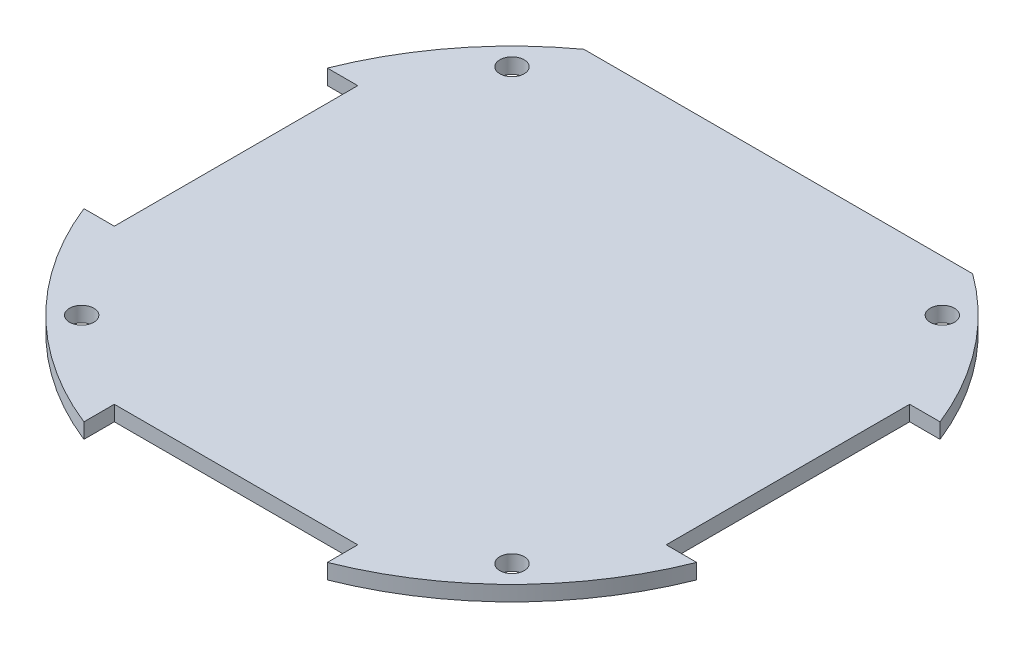
SolidWorks part; units mm, degrees
ref_plane "前视基准面" through (0, 0, 0) normal (0, 0, 1) x (1, 0, 0)
ref_plane "上视基准面" through (0, 0, 0) normal (0, 1, 0) x (1, 0, 0)
ref_plane "右视基准面" through (0, 0, 0) normal (1, 0, 0) x (0, 0, -1)
other "Configuration Table"
sketch "草图1" plane through (0, 0, 0) normal (0, 1, 0) x (1, 0, 0)
  circle A0 centre (0, 0) radius 32.5
  circle A1 centre (0, 0) radius 30 construction
  circle A3 centre (21.2132, 21.2132) radius 1.2
  circle A5 centre (21.2132, -21.2132) radius 1.2
  circle A7 centre (-21.2132, -21.2132) radius 1.2
  circle A9 centre (-21.2132, 21.2132) radius 1.2
  point P15 (0, 0)
  dimension "D1" = 65
  dimension "D2" = 60
extrude "凸台-拉伸1" add sketch "草图1" along normal blind 1.5
sketch "草图2" plane through (0, 1.5, 0) normal (0, 1, 0) x (1, 0, 0)
  line L0 (34.4418, 0) -> (-43.9173, 0) construction
  line L1 (30.2035, 12) -> (27.2035, 12)
  line L2 (27.2035, 12) -> (27.2035, -12)
  line L3 (30.2035, -12) -> (27.2035, -12)
  line L4 (0, 22.8929) -> (0, -32.5) construction
  line L8 (12, -27.2035) -> (-12, -27.2035)
  line L9 (-12, -30.2035) -> (-12, -27.2035)
  line L10 (12, -30.2035) -> (12, -27.2035)
  line L11 (-27.2035, -12) -> (-27.2035, 12)
  line L12 (-30.2035, 12) -> (-27.2035, 12)
  line L13 (-30.2035, -12) -> (-27.2035, -12)
  line L14 (-12, 27.2035) -> (12, 27.2035)
  line L15 (12, 30.2035) -> (12, 27.2035)
  line L16 (-12, 30.2035) -> (-12, 27.2035)
  circle A0 centre (0, 0) radius 32.5 construction
  arc A1 (30.2035, -12) -> (30.2035, 12) centre (0, 0) ccw
  arc A3 (-12, -30.2035) -> (12, -30.2035) centre (0, 0) ccw
  arc A4 (-30.2035, 12) -> (-30.2035, -12) centre (0, 0) ccw
  arc A5 (12, 30.2035) -> (-12, 30.2035) centre (0, 0) ccw
  point P9 (27.2035, 0)
  point P27 (0, 0)
  dimension "D1" = 12
  dimension "D2" = 3
  dimension "D3" = 4
extrude "切除-拉伸1" cut sketch "草图2" against normal through all
sketch "草图3" plane through (0, 1.5, 0) normal (0, 1, 0) x (1, 0, 0)
  line L1 (17, 26.25) -> (-17, 26.25)
  line L2 (17, 26.25) -> (28.1494, 26.25)
  line L3 (28.1494, 26.25) -> (-14.2404, 46.7454)
  line L4 (-14.2404, 46.7454) -> (-27.1497, 26.25)
  line L5 (-27.1497, 26.25) -> (-17, 26.25)
extrude "切除-拉伸2" cut sketch "草图3" against normal through all
sketch "草图4" plane through (0, 0, 0) normal (0, -1, 0) x (1, 0, 0)
  line L0 (0, 28.8846) -> (0, -39.9972) construction
  line L2 (12, 27.2035) -> (-12, 27.2035) construction
  circle A0 centre (3, 22.2035) radius 1.5
  circle A1 centre (3, 18.2035) radius 1.5
  circle A2 centre (-6, 24.2035) radius 1
  circle A6 centre (-3, 24.2035) radius 1
  circle A7 centre (-3, 21.2035) radius 1
  circle A8 centre (-6, 21.2035) radius 1
  dimension "D1" = 3
  dimension "D2" = 3
  dimension "D6" = 2
  dimension "D7" = 2
  dimension "D8" = 2
  dimension "D9" = 3
  dimension "D10" = 6
  dimension "D3" = 4
  dimension "D4" = 5
  dimension "D5" = 3
  dimension "D11" = 3
  dimension "D12" = 3
extrude "切除-拉伸3" cut sketch "草图4" against normal blind 0.1
